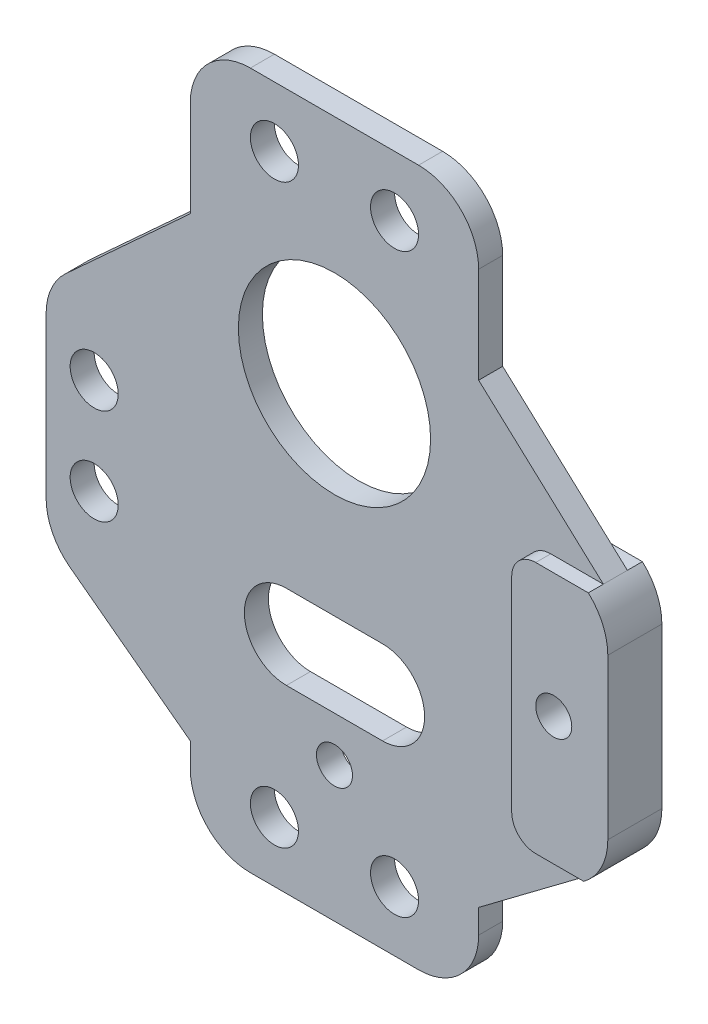
SolidWorks part; units mm, degrees
ref_plane "前视基准面" through (0, 0, 0) normal (0, 0, 1) x (1, 0, 0)
ref_plane "上视基准面" through (0, 0, 0) normal (0, 1, 0) x (1, 0, 0)
ref_plane "右视基准面" through (0, 0, 0) normal (1, 0, 0) x (0, 0, -1)
other "Configuration Table"
ref_plane "基准面1" through (0, 0, 0) normal (0, 0, -1) x (-1, 0, 0)
sketch "草图1" plane through (0, 0, 0) normal (0, 0, -1) x (-1, 0, 0)
  line L0 (-12.803, -22.4015) -> (-12.803, -24.4015)
  line L1 (-7.803, -29.4015) -> (6.197, -29.4015)
  line L2 (11.197, -24.4015) -> (11.197, -22.4015)
  line L3 (11.197, -22.4015) -> (21.197, -14.9015)
  line L4 (23.197, -10.9015) -> (23.197, 2.399)
  line L5 (21.5756, 6.0847) -> (11.197, 15.5985)
  line L6 (11.197, 15.5985) -> (11.197, 23.5985)
  line L7 (6.197, 28.5985) -> (-7.803, 28.5985)
  line L8 (-12.803, 23.5985) -> (-12.803, 15.5985)
  line L9 (-12.803, 15.5985) -> (-23.1817, 6.0847)
  line L10 (-24.803, 2.399) -> (-24.803, -10.9015)
  line L11 (-22.803, -14.9015) -> (-12.803, -22.4015)
  line L12 (3.197, -14.4015) -> (-4.803, -14.4015)
  line L13 (-4.803, -7.4015) -> (3.197, -7.4015)
  circle A0 centre (19.197, -8.4015) radius 2
  circle A1 centre (19.197, -0.4015) radius 2
  circle A2 centre (4.197, 23.5985) radius 2
  circle A3 centre (-5.803, 23.5985) radius 2
  circle A4 centre (-0.803, 9.3485) radius 8
  arc A5 (-12.803, -24.4015) -> (-7.803, -29.4015) centre (-7.803, -24.4015) ccw
  arc A6 (6.197, -29.4015) -> (11.197, -24.4015) centre (6.197, -24.4015) ccw
  arc A7 (21.197, -14.9015) -> (23.197, -10.9015) centre (18.197, -10.9015) ccw
  arc A8 (23.197, 2.399) -> (21.5756, 6.0847) centre (18.197, 2.399) ccw
  arc A9 (11.197, 23.5985) -> (6.197, 28.5985) centre (6.197, 23.5985) ccw
  arc A10 (-7.803, 28.5985) -> (-12.803, 23.5985) centre (-7.803, 23.5985) ccw
  arc A11 (-23.1817, 6.0847) -> (-24.803, 2.399) centre (-19.803, 2.399) ccw
  arc A12 (-24.803, -10.9015) -> (-22.803, -14.9015) centre (-19.803, -10.9015) ccw
  arc A13 (3.197, -7.4015) -> (3.197, -14.4015) centre (3.197, -10.9015) cw
  arc A14 (-4.803, -14.4015) -> (-4.803, -7.4015) centre (-4.803, -10.9015) cw
  circle A15 centre (-20.803, -8.4015) radius 2
  circle A16 centre (-20.803, -0.4015) radius 2
  circle A17 centre (-5.803, -24.4015) radius 2
  circle A18 centre (4.197, -24.4015) radius 2
  circle A19 centre (-0.803, -18.1515) radius 1.5
extrude "凸台-拉伸1" add sketch "草图1" against normal blind 2
sketch "草图2" plane through (0, 0, 2) normal (0, 0, 1) x (1, 0, 0)
  line L0 (23.1817, 6.0847) -> (16.803, 6.0847)
  line L1 (16.803, 6.0847) -> (16.803, -14.9015)
  line L2 (16.803, -14.9015) -> (22.803, -14.9015)
  line L3 (24.803, 2.399) -> (24.803, -10.9015) construction
  line L4 (24.803, 2.399) -> (24.803, -10.9015)
  arc A2 (24.803, 2.399) -> (23.1817, 6.0847) centre (19.803, 2.399) ccw
  arc A4 (22.803, -14.9015) -> (24.803, -10.9015) centre (19.803, -10.9015) ccw
  dimension "D1" = 8
extrude "凸台-拉伸2" add sketch "草图2" against normal mid plane 6.5
sketch "草图3" plane through (0, 0, 2) normal (0, 0, 1) x (1, 0, 0)
  line L0 (24.803, 2.399) -> (24.803, -10.9015) construction
  circle A0 centre (20.303, -4.2513) radius 1.5
  dimension "D1" = 4.5
extrude "切除-拉伸1" cut sketch "草图3" against normal through all both and the other way through all
sketch "草图4" plane through (0, 0, 5.25) normal (0, 0, 1) x (1, 0, 0)
  line L4 (23.1817, 6.0847) -> (16.803, 6.0847)
  line L5 (16.803, 6.0847) -> (16.803, -14.9015)
  line L6 (16.803, -14.9015) -> (22.803, -14.9015)
  line L7 (24.803, -10.9015) -> (24.803, 2.399)
  line L8 (23.1817, 6.0847) -> (16.803, 6.0847)
  line L9 (16.803, 6.0847) -> (16.803, -14.9015)
  line L10 (16.803, -14.9015) -> (22.803, -14.9015)
  line L11 (24.803, -10.9015) -> (24.803, 2.399)
  arc A2 (24.803, 2.399) -> (23.1817, 6.0847) centre (19.803, 2.399) ccw
  arc A3 (22.803, -14.9015) -> (24.803, -10.9015) centre (19.803, -10.9015) ccw
  arc A4 (24.803, 2.399) -> (23.1817, 6.0847) centre (19.803, 2.399) ccw
  arc A5 (22.803, -14.9015) -> (24.803, -10.9015) centre (19.803, -10.9015) ccw
  dimension "D1" = 0
extrude "切除-拉伸2" cut sketch "草图4" against normal blind 2
fillet "圆角1" radius 2 4 edges at (16.803, 6.0847, -0.625) (16.803, -14.9015, -0.625) (16.803, -14.9015, 2.625) (16.803, 6.0847, 2.625)
